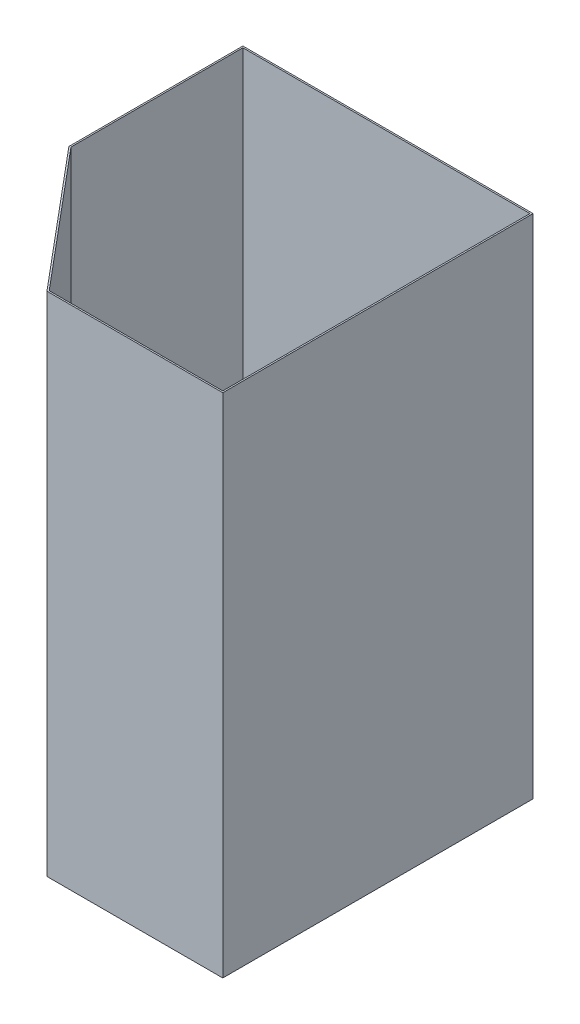
SolidWorks part; units mm, degrees
ref_plane "Спереди" through (0, 0, 0) normal (0, 0, 1) x (1, 0, 0)
ref_plane "Сверху" through (0, 0, 0) normal (0, 1, 0) x (1, 0, 0)
ref_plane "Справа" through (0, 0, 0) normal (1, 0, 0) x (0, 0, -1)
sketch "Эскиз1" plane through (0, 0, 0) normal (0, 1, 0) x (1, 0, 0)
  line L0 (0, 0) -> (-113, 0)
  line L1 (-113, 0) -> (-186.9206, 88.0951)
  line L3 (-186.9206, 88.0951) -> (-186.9206, 200)
  line L4 (-186.9206, 200) -> (0, 200)
  line L5 (0, 200) -> (0, 0)
  dimension "D1" = 200
  dimension "D2" = 130
  dimension "D3" = 113
  dimension "D4" = 115
extrude "Вытянуть-Тонкостенный1" add sketch "Эскиз1" along normal blind 330 thin thin type one direction wall 1
